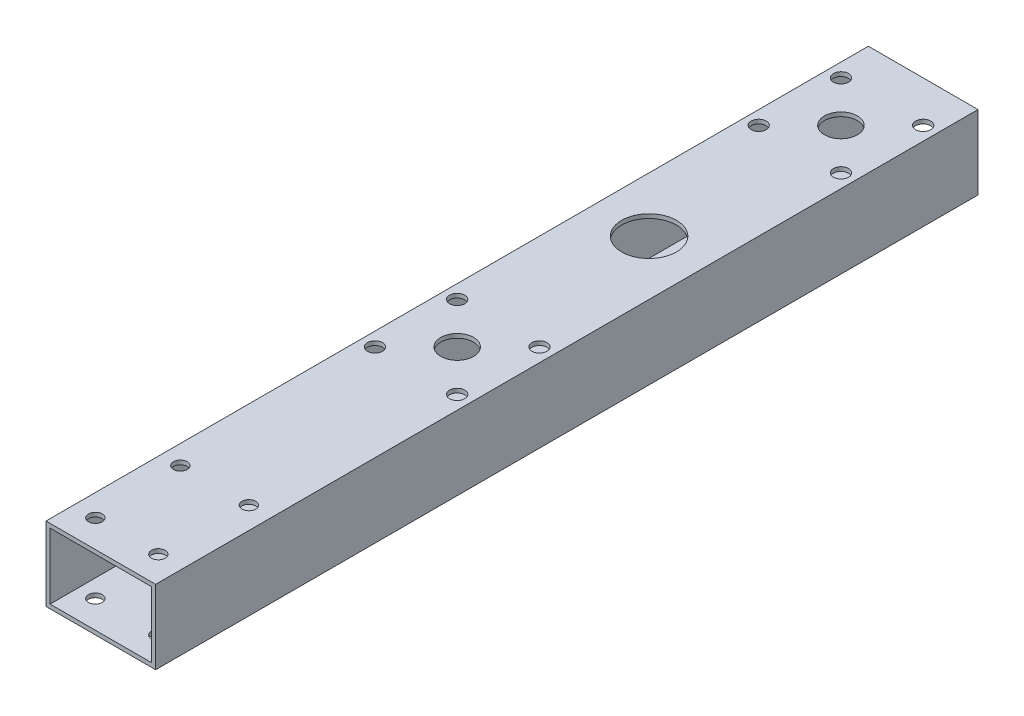
SolidWorks part; units mm, degrees
material "AISI 1020 Acier laminé à froid"
ref_plane "Plan de face" through (0, 0, 0) normal (0, 0, 1) x (1, 0, 0)
ref_plane "Plan de dessus" through (0, 0, 0) normal (0, 1, 0) x (1, 0, 0)
ref_plane "Plan de droite" through (0, 0, 0) normal (1, 0, 0) x (0, 0, -1)
sketch "Esquisse1" plane through (0, 0, 0) normal (0, 0, 1) x (1, 0, 0)
  line L1 (0, 0) -> (40, 0)
  line L2 (0, 0) -> (0, 27)
  line L3 (0, 27) -> (40, 27)
  line L4 (40, 0) -> (40, 27)
  line L5 (1.5, 25.5) -> (38.5, 25.5)
  line L6 (1.5, 25.5) -> (1.5, 1.5)
  line L7 (1.5, 1.5) -> (38.5, 1.5)
  line L8 (38.5, 25.5) -> (38.5, 1.5)
  dimension "D1" = 40
  dimension "D2" = 27
  dimension "D3" = 1.5
  dimension "D4" = 1.5
  dimension "D5" = 1.5
  dimension "D6" = 1.5
extrude "Boss.-Extru.1" add sketch "Esquisse1" along normal blind 300
sketch "Esquisse2" plane through (0, 0, 0) normal (0, 1, 0) x (1, 0, 0)
  line L0 (0, -300) -> (0, 0) construction
  line L1 (40, -300) -> (40, 0) construction
  line L2 (40, -300) -> (0, -300) construction
  line L4 (19.5, -423.1453) -> (19.5, 17.0624) construction
  circle A0 centre (8, -290) radius 2.5
  circle A1 centre (32, -258) radius 2.5
  circle A6 centre (7, -258) radius 2.5
  circle A7 centre (31, -290) radius 2.5
  dimension "D1" = 5
  dimension "D2" = 5
  dimension "D4" = 8
  dimension "D3" = 8
  dimension "D5" = 10
  dimension "D6" = 32
  dimension "D8" = 19.5
extrude "Enlèv. mat.-Extru.1" cut sketch "Esquisse2" along normal through all
sketch "Esquisse3" plane through (0, 0, 0) normal (0, 1, 0) x (1, 0, 0)
  line L0 (0, 0) -> (40, 0) construction
  line L1 (40, -300) -> (40, 0) construction
  line L3 (-30.9776, -100) -> (74.47, -100) construction
  line L4 (0, -300) -> (0, 0) construction
  line L10 (40, 0) -> (0, 0) construction
  circle A0 centre (20, -30) radius 6
  circle A1 centre (5, -15) radius 2.75
  circle A2 centre (20, -100) radius 10
  circle A3 centre (35, -15) radius 2.75
  circle A4 centre (35, -45) radius 2.75
  circle A5 centre (5, -45) radius 2.75
  circle A6 centre (5, -185) radius 2.75
  circle A7 centre (35, -185) radius 2.75
  circle A8 centre (35, -155) radius 2.75
  circle A9 centre (20, -170) radius 6
  circle A10 centre (5, -155) radius 2.75
  point P2 (20, 0)
  dimension "D1" = 12
  dimension "D4" = 5
  dimension "D9" = 20
  dimension "D5" = 5.5
  dimension "D13" = 5.5
  dimension "D14" = 5.5
  dimension "D17" = 5.5
  dimension "D2" = 30
  dimension "D3" = 20
  dimension "D6" = 15
  dimension "D7" = 70
  dimension "D8" = 20
  dimension "D10" = 5
  dimension "D11" = 5
  dimension "D12" = 45
  dimension "D15" = 5
  dimension "D16" = 15
  dimension "D18" = 45
extrude "Enlèv. mat.-Extru.2" cut sketch "Esquisse3" along normal through all
